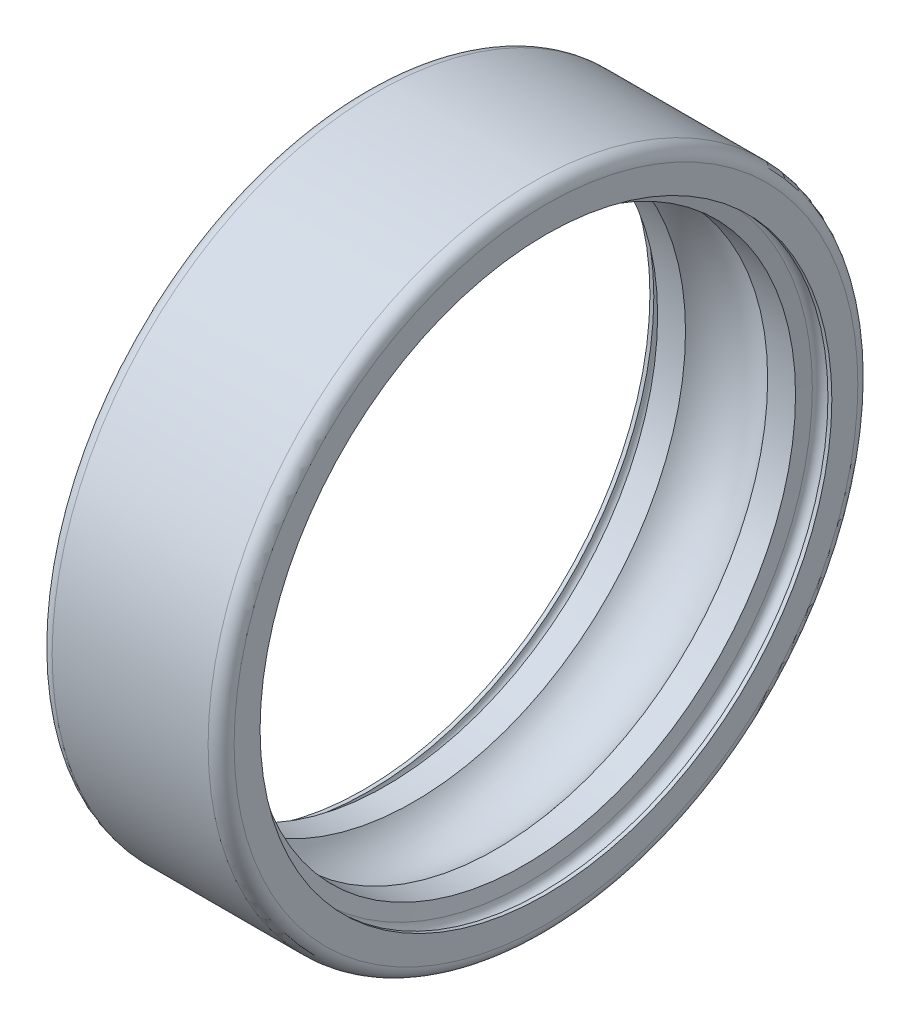
SolidWorks part; units mm, degrees
ref_plane "Front Plane" through (0, 0, 0) normal (0, 0, 1) x (1, 0, 0)
ref_plane "Top Plane" through (0, 0, 0) normal (0, 1, 0) x (1, 0, 0)
ref_plane "Right Plane" through (0, 0, 0) normal (1, 0, 0) x (0, 0, -1)
ref_plane "Plane1"
sketch "Sketch1" plane through (0, 0, 0) normal (0, 0, 1) x (1, 0, 0)
  line L0 (0, 22) -> (0.3, 22)
  line L1 (1.5, 22) -> (1.694, 20.9)
  line L2 (1.694, 20.9) -> (3.8388, 20.9)
  line L3 (10.1612, 20.9) -> (12.306, 20.9)
  line L4 (12.306, 20.9) -> (12.5, 22)
  line L5 (13.7, 22) -> (14, 22)
  line L6 (14, 22) -> (14, 24)
  line L7 (13, 25) -> (1, 25)
  line L8 (0, 24) -> (0, 22)
  line L9 (50, 0) -> (-50, 0) construction
  arc A0 (1.5, 22) -> (0.3, 22) centre (0.9, 22) ccw
  arc A1 (10.1612, 20.9) -> (3.8388, 20.9) centre (7, 18.5) ccw
  arc A2 (13.7, 22) -> (12.5, 22) centre (13.1, 22) ccw
  arc A3 (14, 24) -> (13, 25) centre (13, 24) ccw
  arc A4 (1, 25) -> (0, 24) centre (1, 24) ccw
revolve "Revolução1" add sketch "Sketch1" angle 360 about L9
